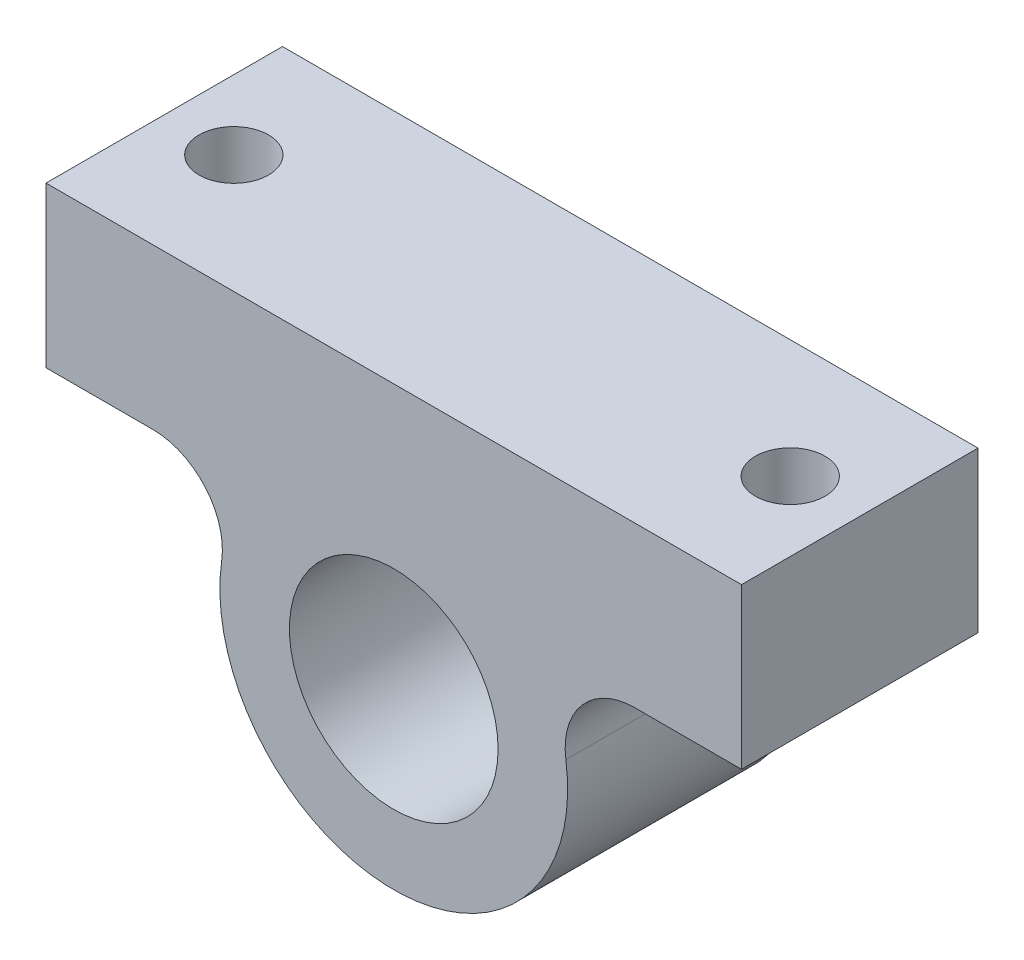
SolidWorks part; units mm, degrees
ref_plane "Front Plane" through (0, 0, 0) normal (0, 0, 1) x (1, 0, 0)
ref_plane "Top Plane" through (0, 0, 0) normal (0, 1, 0) x (1, 0, 0)
ref_plane "Right Plane" through (0, 0, 0) normal (1, 0, 0) x (0, 0, -1)
sketch "Sketch1" plane through (0, 0, 0) normal (0, 0, 1) x (1, 0, 0)
  line L0 (0, -244.5472) -> (0, 11982.8127) construction
  line L1 (-244.5472, 0) -> (11982.8127, 0) construction
  line L2 (-1033.8098, 19) -> (48966.1902, 19) construction
  line L3 (-25, 19) -> (25, 19)
  line L4 (-25, 7.5) -> (-25, 19)
  line L5 (25, 7.5) -> (25, 19)
  line L6 (-25, 7.5) -> (-10, 7.5)
  line L7 (25, 7.5) -> (10, 7.5)
  circle A0 centre (0, 0) radius 7.5
  arc A1 (-10, 7.5) -> (10, 7.5) centre (0, 0) ccw
  dimension "D1" = 15
  dimension "D4" = 5
  dimension "D2" = 19
  dimension "D7" = 50
extrude "Boss-Extrude1" add sketch "Sketch1" along normal blind 17
sketch "Sketch2" plane through (0, 19, 0) normal (0, 1, 0) x (1, 0, 0)
  line L0 (-1020, -8.5) -> (48980, -8.5) construction
  line L1 (-25, -17) -> (-25, 0) construction
  line L2 (0, -1000) -> (0, 49000) construction
  line L3 (25, -17) -> (25, 0) construction
  circle A0 centre (20, -8.5) radius 2.5
  circle A1 centre (-20, -8.5) radius 2.5
  point P5 (-25, -8.5)
  dimension "D1" = 5
  dimension "D2" = 5
extrude "Cut-Extrude1" cut sketch "Sketch2" against normal up to next and the other way through all
fillet "Fillet1" radius 5 1 edges at (-10, 7.5, 8.5)
fillet "Fillet2" radius 5 1 edges at (10, 7.5, 8.5)
